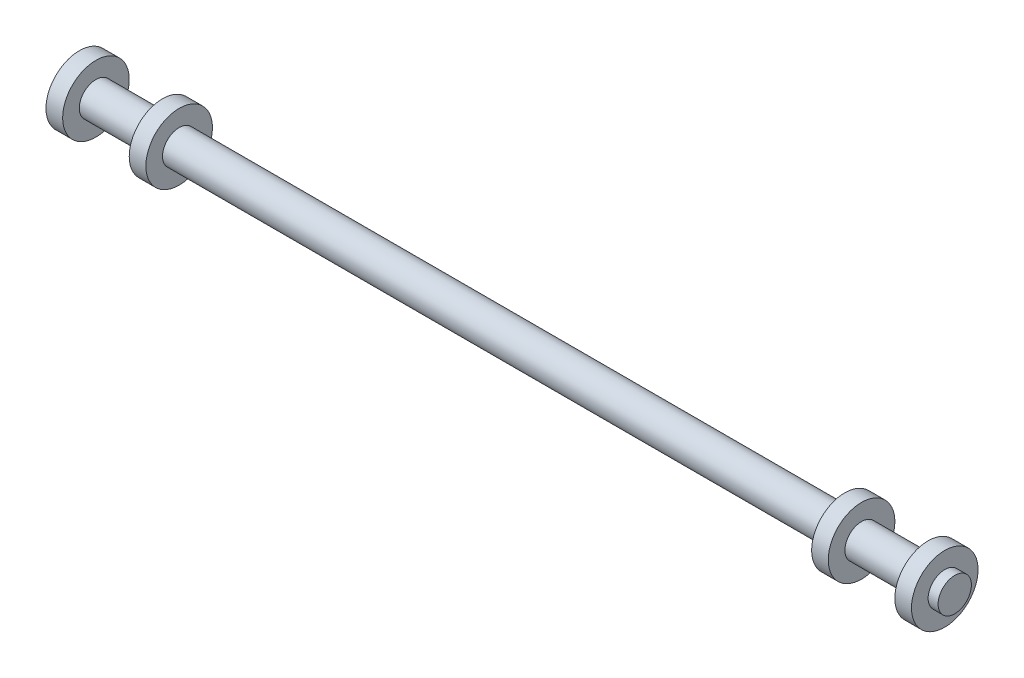
SolidWorks part; units mm, degrees
ref_plane "Front Plane" through (0, 0, 0) normal (0, 0, 1) x (1, 0, 0)
ref_plane "Top Plane" through (0, 0, 0) normal (0, 1, 0) x (1, 0, 0)
ref_plane "Right Plane" through (0, 0, 0) normal (1, 0, 0) x (0, 0, -1)
sketch "Sketch2" plane through (0, 0, 0) normal (0, 0, 1) x (1, 0, 0)
  line L21 (50, 2.5) -> (-50, 2.5)
  line L22 (-50, 2.5) -> (-50, 5)
  line L23 (-50, 5) -> (-52.5, 5)
  line L24 (-52.5, 5) -> (-52.5, 2.5)
  line L25 (-52.5, 2.5) -> (-62.5, 2.5)
  line L26 (-62.5, 2.5) -> (-62.5, 5)
  line L27 (-62.5, 5) -> (-65, 5)
  line L28 (-65, 5) -> (-65, 2.5)
  line L29 (-65, 2.5) -> (-66.5, 2.5)
  line L30 (-66.5, 2.5) -> (-66.5, 0)
  line L31 (-66.5, 0) -> (66.5, 0)
  line L32 (0, -55) -> (0, 55) construction
  line L33 (66.5, 2.5) -> (66.5, 0)
  line L34 (65, 2.5) -> (66.5, 2.5)
  line L35 (65, 5) -> (65, 2.5)
  line L36 (62.5, 5) -> (65, 5)
  line L37 (62.5, 2.5) -> (62.5, 5)
  line L38 (52.5, 2.5) -> (62.5, 2.5)
  line L39 (52.5, 5) -> (52.5, 2.5)
  line L40 (50, 5) -> (52.5, 5)
  line L41 (50, 2.5) -> (50, 5)
  point P2 (0, 0)
  point P27 (0, 2.5)
  dimension "D1" = 2.5
  dimension "D2" = 2.5
  dimension "D3" = 2.5
  dimension "D4" = 100
  dimension "D5" = 10
  dimension "D6" = 1.5
revolve "Revolve1" add sketch "Sketch2" angle 360 about L31
